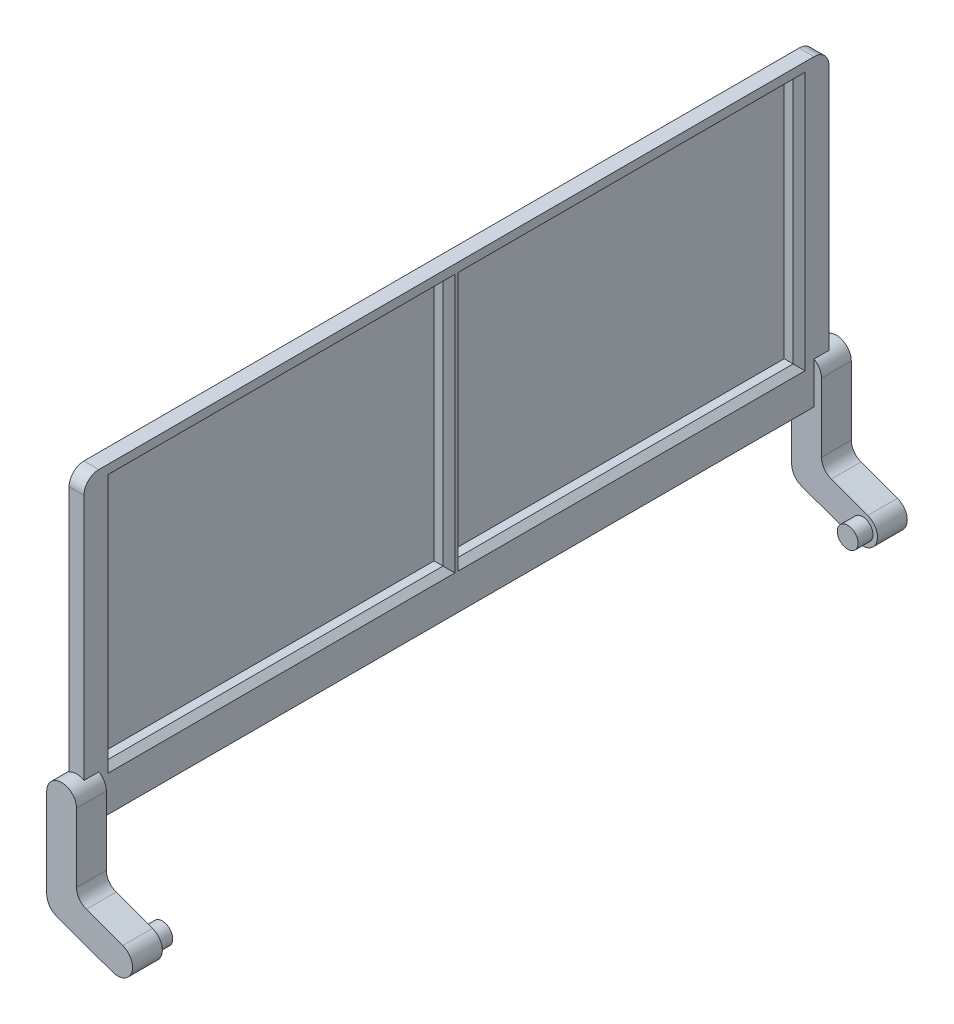
SolidWorks part; units mm, degrees
ref_plane "Front Plane" through (0, 0, 0) normal (0, 0, 1) x (1, 0, 0)
ref_plane "Top Plane" through (0, 0, 0) normal (0, 1, 0) x (1, 0, 0)
ref_plane "Right Plane" through (0, 0, 0) normal (1, 0, 0) x (0, 0, -1)
sketch "Sketch2" plane through (0, 0, 0) normal (1, 0, 0) x (0, 0, -1)
  line L0 (0, 0) -> (0, 101.8) construction
  line L1 (-120, 101.8) -> (120, 101.8)
  line L2 (-125, 96.8) -> (-125, 0)
  line L3 (-125, 0) -> (125, 0)
  line L4 (125, 96.8) -> (125, 0)
  line L5 (2.5, 96.8) -> (2.5, 14)
  line L6 (-115, 96.8) -> (-2.5, 96.8)
  line L7 (-115, 96.8) -> (-115, 14)
  line L8 (-115, 14) -> (-2.5, 14)
  line L9 (-2.5, 96.8) -> (-2.5, 14)
  line L10 (115, 96.8) -> (115, 14)
  line L11 (115, 96.8) -> (2.5, 96.8)
  line L12 (115, 14) -> (2.5, 14)
  arc A0 (-120, 101.8) -> (-125, 96.8) centre (-120, 96.8) ccw
  arc A1 (120, 101.8) -> (125, 96.8) centre (120, 96.8) cw
  point P19 (125, 101.8)
  dimension "D7" = 5
  dimension "D1" = 250
  dimension "D2" = 101.8
  dimension "D3" = 5
  dimension "D4" = 14
  dimension "D5" = 10
  dimension "D6" = 5
extrude "Boss-Extrude1" add sketch "Sketch2" against normal blind 5
chamfer "Chamfer1" distance 2 angle 45 8 edges at (0, 55.4, 2.5) (0, 14, 58.75) (0, 55.4, 115) (0, 96.8, 58.75) (0, 55.4, -2.5) (0, 96.8, -58.75) (0, 14, -58.75) (0, 55.4, -115)
sketch "Sketch3" plane through (0, 0, 125) normal (0, 0, 1) x (1, 0, 0)
  line L0 (-5, 1.8199) -> (-5, 0)
  line L1 (-5, 96.8) -> (-5, 0) construction
  line L2 (-5, 0) -> (0, 0)
  line L3 (0, 0) -> (-5, 1.8199)
  line L4 (0, 96.8) -> (0, 0) construction
  dimension "D1" = 110
extrude "Cut-Extrude1" cut sketch "Sketch3" against normal through all
sketch "Sketch4" plane through (0, 0, 125) normal (0, 0, 1) x (1, 0, 0)
  line L0 (-2.5, 9.6) -> (-2.5, -20.4) construction
  line L1 (-2.5, -20.4) -> (16.2939, -27.2404) construction
  line L2 (0, 96.8) -> (0, 0) construction
  line L3 (-5, 101.8) -> (0, 101.8) construction
  line L4 (-7.5, 9.6) -> (-7.5, -20.4)
  line L5 (-4.2101, -25.0985) -> (14.5838, -31.9389)
  line L6 (2.5, 9.6) -> (2.5, -13.3979)
  line L7 (5.7899, -18.0964) -> (18.004, -22.5419)
  line L8 (2.5, 9.6) -> (2.5, -16.899) construction
  line L9 (2.5, -16.899) -> (18.004, -22.5419) construction
  line L10 (-7.5, 9.6) -> (-7.5, -23.901) construction
  line L11 (-7.5, -23.901) -> (14.5838, -31.9389) construction
  arc A0 (-7.5, 9.6) -> (2.5, 9.6) centre (-2.5, 9.6) cw
  arc A1 (14.5838, -31.9389) -> (18.004, -22.5419) centre (16.2939, -27.2404) ccw
  arc A2 (2.5, -13.3979) -> (5.7899, -18.0964) centre (7.5, -13.3979) ccw
  arc A3 (-7.5, -20.4) -> (-4.2101, -25.0985) centre (-2.5, -20.4) ccw
  point P7 (-2.5, 101.8)
  dimension "D8" = 5
  dimension "D1" = 30
  dimension "D2" = 20
  dimension "D3" = 2.5
  dimension "D4" = 92.2
  dimension "D5" = 110
  dimension "D6" = 5
  dimension "D7" = 5
extrude "Boss-Extrude2" add sketch "Sketch4" along normal mid plane 10 separate body
sketch "Sketch5" plane through (0, 0, 120) normal (0, 0, -1) x (-1, 0, 0)
  circle A0 centre (-16.2939, -27.2404) radius 3.5
  dimension "D1" = 7
extrude "Boss-Extrude3" add sketch "Sketch5" along normal mid plane 10
mirror "Mirror1" about plane through (0, 0, 0) normal (0, 0, 1) of bodies 104
sketch "Sketch7" plane through (-5, 0, 0) normal (-1, 0, 0) x (0, 0, 1)
  line L0 (115, 96.8) -> (115, 14) construction
  line L1 (2.5, 96.8) -> (115, 96.8) construction
  line L2 (2.5, 14) -> (2.5, 96.8) construction
  line L3 (115, 14) -> (2.5, 14) construction
  line L4 (-115, 14) -> (-115, 96.8) construction
  line L5 (-115, 96.8) -> (-2.5, 96.8) construction
  line L6 (-2.5, 96.8) -> (-2.5, 14) construction
  line L7 (-2.5, 14) -> (-115, 14) construction
  line L8 (115, 96.8) -> (115, 14)
  line L9 (2.5, 96.8) -> (115, 96.8)
  line L10 (2.5, 14) -> (2.5, 96.8)
  line L11 (115, 14) -> (2.5, 14)
  line L12 (-115, 14) -> (-115, 96.8)
  line L13 (-115, 96.8) -> (-2.5, 96.8)
  line L14 (-2.5, 96.8) -> (-2.5, 14)
  line L15 (-2.5, 14) -> (-115, 14)
extrude "Boss-Extrude5" add sketch "Sketch7" along normal blind 1
